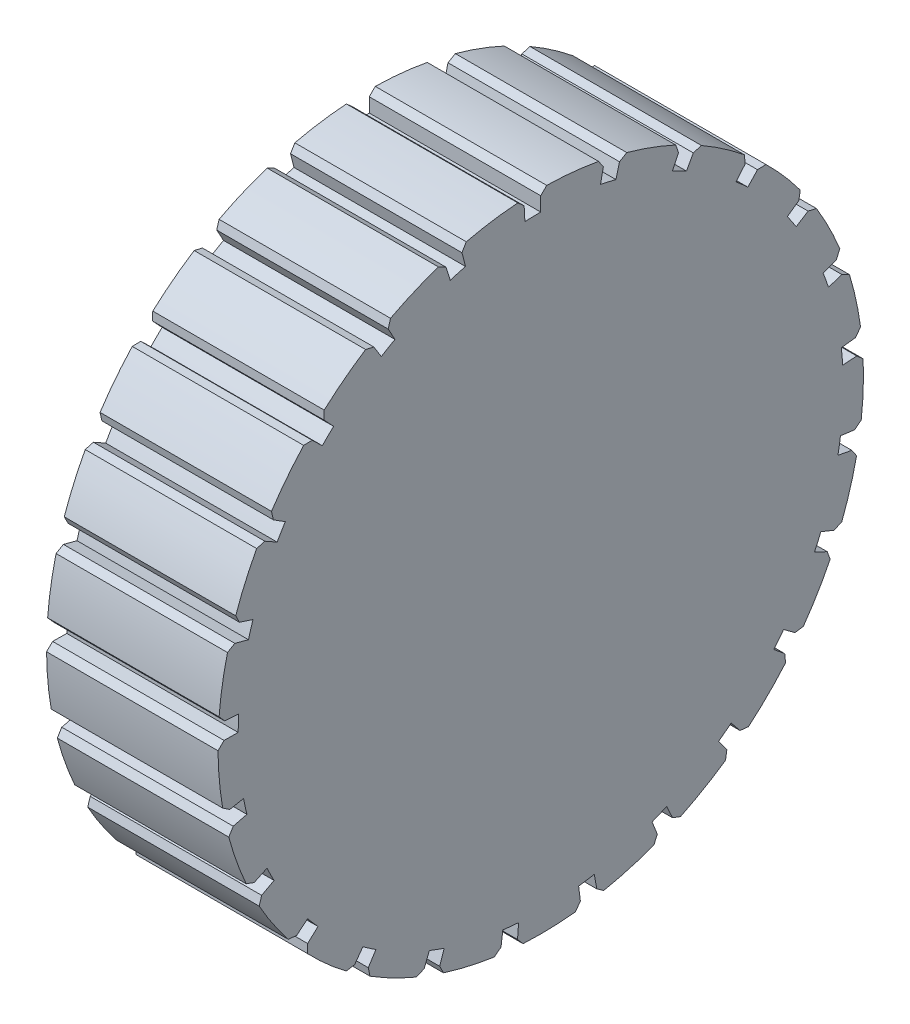
SolidWorks part; units mm, degrees
ref_plane "Front Plane" through (0, 0, 0) normal (0, 0, 1) x (1, 0, 0)
ref_plane "Top Plane" through (0, 0, 0) normal (0, 1, 0) x (1, 0, 0)
ref_plane "Right Plane" through (0, 0, 0) normal (1, 0, 0) x (0, 0, -1)
sketch "Sketch1" plane through (0, 0, 0) normal (1, 0, 0) x (0, 0, -1)
  circle A0 centre (0, 0) radius 3.2
  dimension "D1" = 6.4
extrude "Boss-Extrude1" add sketch "Sketch1" along normal mid plane 1.7
sketch "Sketch2" plane through (0.85, 0, 0) normal (1, 0, 0) x (0, 0, -1)
  line L0 (0, 3.2) -> (0, 3)
  line L2 (-0.157, 2.9959) -> (-0.1675, 3.1956)
  arc A0 (0, 3) -> (-0.157, 2.9959) centre (0, 0) ccw
  circle A1 centre (0, 0) radius 3.2 construction
  arc A2 (0, 3.2) -> (-0.1675, 3.1956) centre (0, 0) ccw
  dimension "D1" = 6
  dimension "D2" = 3
  dimension "D3" = 0.2
  dimension "D4" = 0.1997
extrude "Cut-Extrude1" cut sketch "Sketch2" against normal up to next contours L0 A0 L2 A2
chamfer "Chamfer1" distance 0.06 angle 45 1 edges at (0, 3.1956, 0.1675)
chamfer "Chamfer2" distance 0.06 angle 45 1 edges at (0, 3.2, 0)
pattern_circular "CirPattern1" count 25 over 360 about axis through (0, 0, 0) along (1, 0, 0) of "Cut-Extrude1", "Chamfer2", "Chamfer1"
